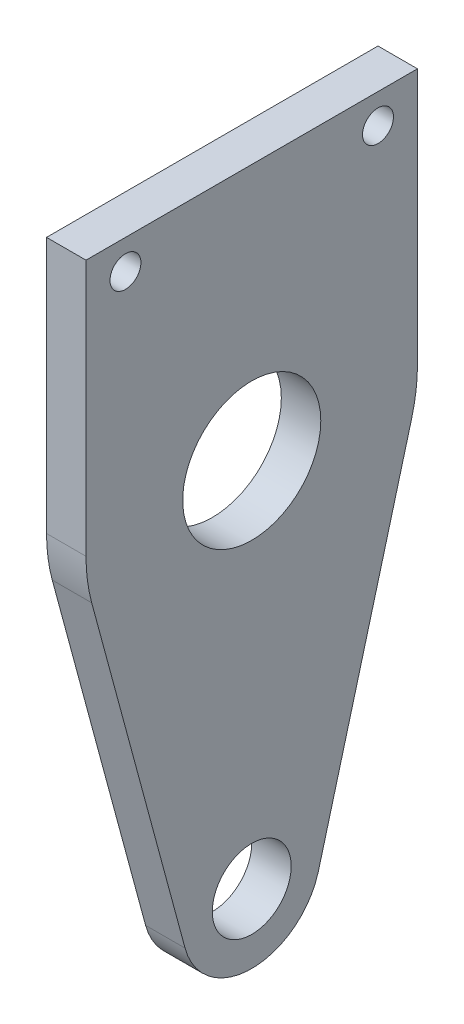
SolidWorks part; units mm, degrees
ref_plane "Front Plane" through (0, 0, 0) normal (0, 0, 1) x (1, 0, 0)
ref_plane "Top Plane" through (0, 0, 0) normal (0, 1, 0) x (1, 0, 0)
ref_plane "Right Plane" through (0, 0, 0) normal (1, 0, 0) x (0, 0, -1)
sketch "Sketch1" plane through (0, 0, 0) normal (1, 0, 0) x (0, 0, -1)
  line L0 (0, 0) -> (0, 59.69) construction
  line L1 (-10.7284, -2.8963) -> (-25.7482, 52.7388)
  line L2 (-9.525, 91.439) -> (-26.67, 91.439) construction
  line L3 (25.7482, 52.7388) -> (10.7284, -2.8963)
  line L4 (-34.29, 100.964) -> (-14.2875, 100.964)
  line L5 (-9.525, 91.439) -> (9.525, 91.439) construction
  line L6 (-9.525, 91.439) -> (-9.525, 69.976) construction
  line L7 (-9.525, 69.976) -> (9.525, 69.976) construction
  line L8 (9.525, 91.439) -> (9.525, 69.976) construction
  line L9 (6.35, 121.9983) -> (6.35, 134.6475)
  line L10 (49.3374, 114.0608) -> (49.3374, 4.4598)
  line L11 (49.3374, 4.4598) -> (113.7518, 4.4598)
  line L12 (113.7518, 114.0608) -> (113.7518, 4.4598)
  line L13 (-34.29, 100.964) -> (-34.29, 110.489)
  line L14 (-34.29, 110.489) -> (34.29, 110.489)
  line L15 (34.29, 100.964) -> (34.29, 110.489)
  line L16 (-34.29, 100.964) -> (34.29, 110.489) construction
  line L17 (-34.29, 110.489) -> (34.29, 100.964) construction
  line L18 (-26.67, 91.439) -> (-26.67, 100.964)
  line L19 (-6.35, 100.964) -> (-6.35, 91.439) construction
  line L20 (26.67, 100.964) -> (26.67, 91.439)
  line L21 (26.67, 91.439) -> (9.525, 91.439) construction
  line L22 (-26.67, 91.439) -> (-26.67, 59.69)
  line L23 (26.67, 91.439) -> (26.67, 59.69)
  line L24 (-14.2875, 100.964) -> (14.2875, 100.964)
  line L25 (-14.2875, 100.964) -> (-14.2875, 108.9015)
  line L26 (-14.2875, 108.9015) -> (14.2875, 108.9015)
  line L27 (14.2875, 100.964) -> (14.2875, 108.9015)
  line L28 (-14.2875, 100.964) -> (14.2875, 108.9015) construction
  line L29 (-14.2875, 108.9015) -> (14.2875, 100.964) construction
  line L30 (-11.9062, 91.439) -> (-11.9062, 95.0108) construction
  line L31 (6.35, 100.964) -> (6.35, 91.439) construction
  line L32 (-11.9062, 95.0108) -> (-6.35, 95.0108) construction
  line L33 (6.35, 95.0108) -> (11.9062, 95.0108) construction
  line L34 (11.9062, 95.0108) -> (11.9062, 91.439) construction
  line L35 (-12.7, 91.439) -> (-12.7, 95.0108) construction
  line L36 (-12.7, 95.0108) -> (-11.9062, 95.0108) construction
  line L37 (11.9062, 95.0108) -> (12.7, 95.0108)
  line L38 (12.7, 95.0108) -> (12.7, 91.439) construction
  line L39 (-7.1438, 95.0108) -> (-7.1437, 100.1702) construction
  line L40 (7.1437, 100.1702) -> (7.1438, 95.0108) construction
  line L41 (-7.1437, 100.1702) -> (-9.525, 100.1702) construction
  line L42 (-9.525, 100.1702) -> (-9.525, 100.964) construction
  line L43 (7.1437, 100.1702) -> (9.525, 100.1702) construction
  line L44 (9.525, 100.1702) -> (9.525, 100.964) construction
  line L45 (-14.2875, 108.9015) -> (-14.2875, 110.489)
  line L46 (14.2875, 108.9015) -> (14.2875, 110.489)
  line L47 (-7.62, 108.9015) -> (-7.62, 121.9983)
  line L48 (7.62, 108.9015) -> (7.62, 121.9983)
  line L49 (-19.8438, 110.489) -> (-19.8438, 114.0608)
  line L50 (-19.8438, 114.0608) -> (-7.62, 114.0608)
  line L51 (7.62, 114.0608) -> (19.8438, 114.0608)
  line L52 (19.8438, 114.0608) -> (19.8438, 110.489)
  line L53 (-12.7, 114.0608) -> (-12.7, 108.9015)
  line L54 (12.7, 108.9015) -> (12.7, 114.0608)
  line L55 (19.8438, 114.0608) -> (149.8944, 114.0608)
  line L56 (149.8944, 114.0608) -> (149.8944, 120.4108)
  line L57 (149.8944, 120.4108) -> (15.5575, 120.4108)
  line L58 (14.2875, 120.4108) -> (14.2875, 114.0608)
  line L59 (-19.8438, 114.0608) -> (-77.6474, 114.0608)
  line L60 (-77.6474, 114.0608) -> (-77.6474, 120.4108)
  line L61 (-77.6474, 120.4108) -> (-15.5575, 120.4108)
  line L62 (-14.2875, 120.4108) -> (-14.2875, 114.0608)
  line L63 (14.2875, 100.964) -> (34.29, 100.964)
  line L64 (-14.2875, 120.4108) -> (-15.5575, 120.4108)
  line L65 (-15.5575, 120.4108) -> (-15.5575, 121.9983)
  line L66 (-15.5575, 121.9983) -> (15.5575, 121.9983)
  line L67 (15.5575, 121.9983) -> (15.5575, 120.4108)
  line L68 (15.5575, 120.4108) -> (14.2875, 120.4108)
  line L69 (-26.67, 96.2015) -> (26.67, 96.2015) construction
  line L70 (41.275, 0) -> (41.275, 114.0608) construction
  line L71 (-6.35, 121.9983) -> (-6.35, 134.6475)
  line L72 (-15.5575, 134.6475) -> (15.5575, 134.6475)
  line L73 (-15.5575, 134.6475) -> (-15.5575, 136.235)
  line L74 (-15.5575, 136.235) -> (-14.2875, 136.235)
  line L75 (-14.2875, 136.235) -> (-14.2875, 142.585)
  line L76 (-14.2875, 142.585) -> (14.2875, 142.585)
  line L77 (14.2875, 142.585) -> (14.2875, 136.235)
  line L78 (14.2875, 136.235) -> (15.5575, 136.235)
  line L79 (15.5575, 136.235) -> (15.5575, 134.6475)
  line L80 (-6.35, 128.3229) -> (6.35, 128.3229)
  line L81 (81.5446, 4.4598) -> (81.5446, 148.5732)
  line L82 (-38.1, 123.5604) -> (38.1, 123.5604)
  line L83 (-38.1, 123.5604) -> (-38.1, 133.0854)
  line L84 (-38.1, 133.0854) -> (38.1, 133.0854)
  line L85 (38.1, 123.5604) -> (38.1, 133.0854)
  line L86 (-38.1, 123.5604) -> (38.1, 133.0854) construction
  line L87 (-38.1, 133.0854) -> (38.1, 123.5604) construction
  line L88 (-47.1725, 104.8631) -> (-47.1725, 139.3984) construction
  line L89 (-59.8725, 98.3506) -> (-34.4725, 98.3506)
  line L90 (-59.8725, 98.3506) -> (-59.8725, 111.3756)
  line L91 (-59.8725, 111.3756) -> (-34.4725, 111.3756)
  line L92 (-34.4725, 98.3506) -> (-34.4725, 111.3756)
  line L93 (-59.8725, 98.3506) -> (-34.4725, 111.3756) construction
  line L94 (-59.8725, 111.3756) -> (-34.4725, 98.3506) construction
  line L95 (72.6546, 121.1211) -> (90.4346, 121.1211)
  line L96 (72.6546, 121.1211) -> (72.6546, 140.1711)
  line L97 (72.6546, 140.1711) -> (90.4346, 140.1711)
  line L98 (90.4346, 121.1211) -> (90.4346, 140.1711)
  line L99 (72.6546, 121.1211) -> (90.4346, 140.1711) construction
  line L100 (72.6546, 140.1711) -> (90.4346, 121.1211) construction
  line L101 (-51.935, 120.4108) -> (-51.935, 151.9491)
  line L102 (-42.41, 120.4108) -> (-42.41, 151.9491)
  line L103 (-14.2875, 142.585) -> (-74.0025, 142.585)
  line L104 (-74.0025, 142.585) -> (-74.0025, 136.235)
  line L105 (-74.0025, 136.235) -> (-15.5575, 136.235)
  circle A0 centre (0, 0) radius 41.275 construction
  circle A1 centre (0, 0) radius 34.29 construction
  circle A2 centre (0, 59.69) radius 25.4 construction
  circle A3 centre (0, 0) radius 6.35
  circle A4 centre (0, 0) radius 11.1125
  circle A5 centre (0, 59.69) radius 6.35 construction
  circle A6 centre (0, 59.69) radius 11.1125
  circle A7 centre (0, 59.69) radius 26.67
  point P11 (0, 105.7265)
  point P33 (0, 104.9327)
  point P99 (0, 142.585)
  point P106 (0, 134.6475)
  point P109 (0, 128.3229)
  point P116 (-47.1725, 104.8631)
  point P121 (81.5446, 130.6461)
  point P126 (81.5446, 4.4598)
  point P138 (-20.32, 96.2015)
  point P139 (20.32, 96.2015)
  dimension "D1" = 82.55
  dimension "D2" = 68.58
  dimension "D3" = 12.7
  dimension "D4" = 22.225
  dimension "D5" = 50.8
  dimension "D6" = 12.7
  dimension "D8" = 22.225
  dimension "D14" = 53.34
  dimension "D7" = 59.69
  dimension "D9" = 19.05
  dimension "D10" = 31.749
  dimension "D11" = 21.463
  dimension "D12" = 109.601
  dimension "D13" = 64.4144
  dimension "D15" = 9.525
  dimension "D16" = 68.58
  dimension "D17" = 9.525
  dimension "D18" = 7.9375
  dimension "D19" = 28.575
  dimension "D20" = 3.5719
  dimension "D21" = 0.7937
  dimension "D22" = 0.7937
  dimension "D23" = 23.8125
  dimension "D24" = 12.7
  dimension "D25" = 14.2875
  dimension "D26" = 6.35
  dimension "D27" = 19.05
  dimension "D28" = 0.7937
  dimension "D29" = 15.24
  dimension "D30" = 39.6875
  dimension "D31" = 3.5719
  dimension "D32" = 25.4
  dimension "D33" = 6.35
  dimension "D34" = 6.35
  dimension "D35" = 28.575
  dimension "D36" = 1.5875
  dimension "D37" = 31.115
  dimension "D38" = 12.7
  dimension "D39" = 12.6492
  dimension "D40" = 1.5875
  dimension "D41" = 28.575
  dimension "D42" = 31.115
  dimension "D43" = 7.9375
  dimension "D44" = 9.525
  dimension "D45" = 76.2
  dimension "D46" = 19.05
  dimension "D47" = 17.78
  dimension "D48" = 9.525
  dimension "D49" = 25.4
  dimension "D50" = 6.35
extrude "Boss-Extrude1" add sketch "Sketch1" along normal blind 6.35
hole_wizard "#10 Clearance Hole1" positions "Sketch3" profile "Sketch2" hole size "#10" standard "ANSI Inch" end condition through all
sketch "Sketch3" plane through (0, 0, 0) normal (-1, 0, 0) x (0, 0, 1)
  point P0 (20.32, 96.2015)
  point P3 (-20.32, 96.2015)
sketch "Sketch2" plane through (0, 96.2015, 20.32) normal (0, 1, 0) x (0, 0, 1)
  line L0 (0, 0) -> (0, 6.35)
  line L1 (0, 6.35) -> (2.4892, 6.35)
  line L2 (2.4892, 6.35) -> (2.4892, 0)
  line L5 (2.4892, 0) -> (0, 0)
  line L11 (0, -6.35) -> (0, 107.95) construction
  dimension "Thru Hole Dia." = 4.9784
  dimension "Thru Hole Depth" = 6.35
equation "\"D7@Sketch1\"=(\"D2@Sketch1\"+\"D5@Sketch1\")/2"
equation "\"D5@Sketch1\"=40/20"
